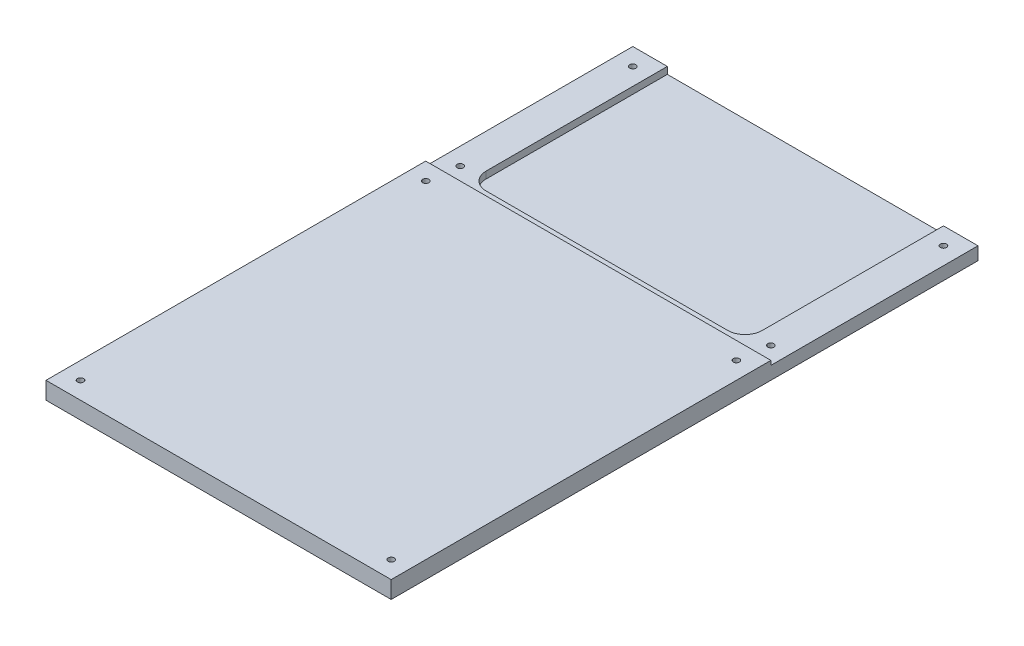
SolidWorks part; units mm, degrees
ref_plane "Front" through (0, 0, 0) normal (0, 0, 1) x (1, 0, 0)
ref_plane "Top" through (0, 0, 0) normal (0, 1, 0) x (1, 0, 0)
ref_plane "Right" through (0, 0, 0) normal (1, 0, 0) x (0, 0, -1)
sketch "Sketch1" plane through (0, 0, 0) normal (0, 1, 0) x (1, 0, 0)
  line L1 (0, 0) -> (127, 0)
  line L2 (0, 0) -> (0, 215.9)
  line L3 (0, 215.9) -> (127, 215.9)
  line L4 (127, 0) -> (127, 215.9)
  dimension "D1" = 215.9
  dimension "D2" = 127
extrude "Boss-Extrude1" add sketch "Sketch1" along normal blind 6.35
sketch "Sketch3" plane through (0, 6.35, 0) normal (0, 1, 0) x (1, 0, 0)
  line L0 (127, 0) -> (127, 215.9) construction
  line L1 (0, 215.9) -> (127, 215.9)
  line L2 (0, 215.9) -> (0, 139.7)
  line L3 (0, 139.7) -> (127, 139.7)
  line L4 (127, 215.9) -> (127, 139.7)
  dimension "D1" = 76.2
extrude "Cut-Extrude1" cut sketch "Sketch3" against normal blind 1.5875
hole_wizard "#43 (0.089) Diameter Hole1" positions "Sketch4" profile "Sketch5" hole size "#43" standard "ANSI Inch" end condition through all
sketch "Sketch4" plane through (0, 4.7625, 0) normal (0, 1, 0) x (1, 0, 0)
  line L0 (127, 215.9) -> (0, 215.9) construction
  line L1 (0, 215.9) -> (0, 139.7) construction
  line L2 (63.5, 139.7) -> (63.5, 215.9) construction
  line L3 (0, 139.7) -> (127, 139.7) construction
  line L8 (0, 177.8) -> (127, 177.8) construction
  line L9 (127, 139.7) -> (127, 215.9) construction
  point P0 (6.35, 209.55)
  point P28 (6.35, 146.05)
  point P30 (120.65, 146.05)
  point P31 (120.65, 209.55)
  dimension "D1" = 6.35
  dimension "D2" = 6.35
sketch "Sketch5" plane through (6.35, 4.7625, -209.55) normal (1, 0, 0) x (0, 0, 1)
  line L0 (0, 0) -> (0, 4.7625)
  line L1 (0, 4.7625) -> (1.1303, 4.7625)
  line L2 (1.1303, 4.7625) -> (1.1303, 0)
  line L5 (1.1303, 0) -> (0, 0)
  line L11 (0, -6.35) -> (0, 107.95) construction
  dimension "Thru Hole Dia." = 2.2606
  dimension "Thru Hole Depth" = 4.7625
hole_wizard "#43 (0.089) Diameter Hole2" positions "Sketch6" profile "Sketch7" hole size "#43" standard "ANSI Inch" end condition through all
sketch "Sketch6" plane through (0, 6.35, 0) normal (0, 1, 0) x (1, 0, 0)
  line L0 (0, 0) -> (127, 0) construction
  line L1 (0, 139.7) -> (0, 0) construction
  line L3 (63.5, 0) -> (63.5, 139.7) construction
  line L4 (0, 139.7) -> (127, 139.7) construction
  line L6 (127, 69.85) -> (0, 69.85) construction
  line L7 (127, 0) -> (127, 139.7) construction
  point P0 (6.35, 6.35)
  point P21 (120.65, 6.35)
  point P23 (6.35, 133.35)
  point P24 (120.65, 133.35)
  dimension "D1" = 6.35
  dimension "D2" = 6.35
sketch "Sketch7" plane through (6.35, 6.35, -6.35) normal (1, 0, 0) x (0, 0, 1)
  line L0 (0, 0) -> (0, 6.35)
  line L1 (0, 6.35) -> (1.1303, 6.35)
  line L2 (1.1303, 6.35) -> (1.1303, 0)
  line L5 (1.1303, 0) -> (0, 0)
  line L11 (0, -6.35) -> (0, 107.95) construction
  dimension "Thru Hole Dia." = 2.2606
  dimension "Thru Hole Depth" = 6.35
sketch "Sketch8" plane through (0, 4.7625, 0) normal (0, 1, 0) x (1, 0, 0)
  line L0 (127, 215.9) -> (0, 215.9) construction
  line L1 (12.7, 215.9) -> (114.3, 215.9)
  line L2 (12.7, 215.9) -> (12.7, 142.875)
  line L3 (12.7, 142.875) -> (114.3, 142.875)
  line L4 (114.3, 215.9) -> (114.3, 142.875)
  line L5 (0, 215.9) -> (0, 139.7) construction
  line L6 (127, 139.7) -> (127, 215.9) construction
  line L7 (0, 139.7) -> (127, 139.7) construction
  dimension "D1" = 12.7
  dimension "D2" = 12.7
  dimension "D3" = 3.175
extrude "Cut-Extrude2" cut sketch "Sketch8" against normal blind 2.54
fillet "Fillet1" radius 6.35 2 edges at (12.7, 3.4925, -142.875) (114.3, 3.4925, -142.875)
